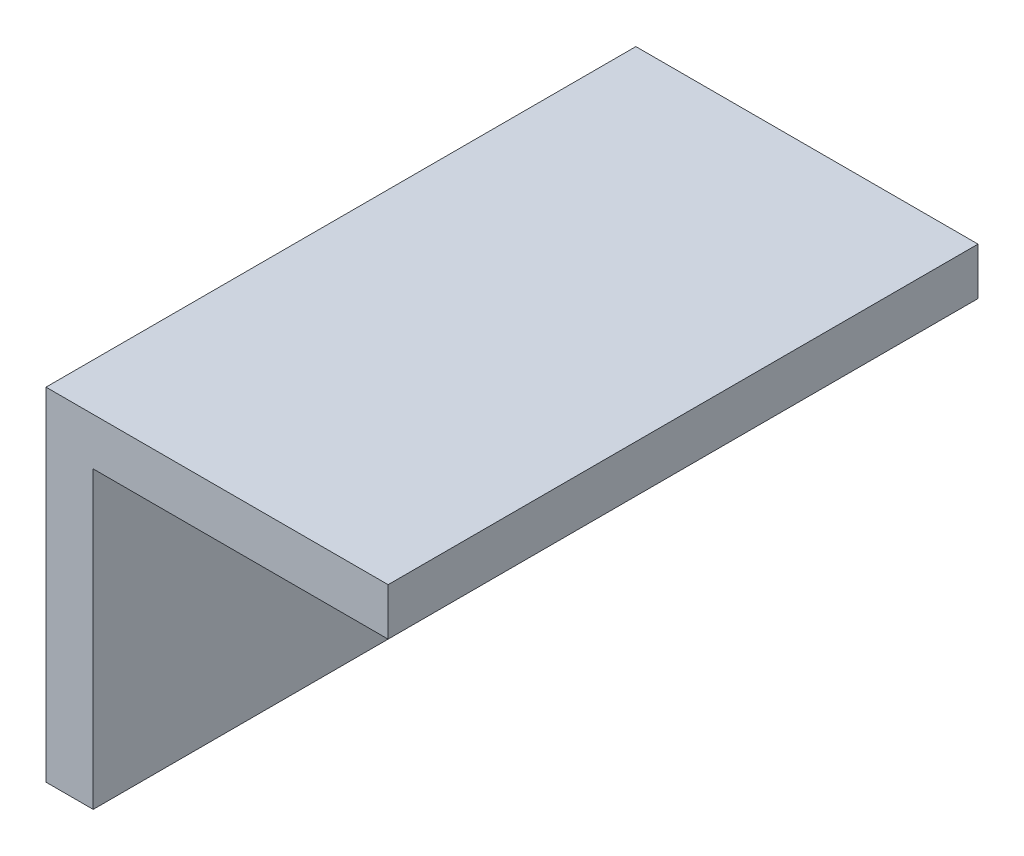
SolidWorks part; units mm, degrees
material "PLA"
ref_plane "Front Plane" through (0, 0, 0) normal (0, 0, 1) x (1, 0, 0)
ref_plane "Top Plane" through (0, 0, 0) normal (0, 1, 0) x (1, 0, 0)
ref_plane "Right Plane" through (0, 0, 0) normal (1, 0, 0) x (0, 0, -1)
sketch "Sketch1" plane through (0, 0, 0) normal (0, 0, 1) x (1, 0, 0)
  line L0 (0, 0) -> (50, 0)
  line L1 (0, 0) -> (0, -50)
  line L2 (-8, 8) -> (-8, -50)
  line L3 (-8, 8) -> (50, 8)
  line L4 (0, -50) -> (-8, -50)
  line L5 (50, 0) -> (50, 8)
  dimension "D1" = 50
  dimension "D2" = 50
  dimension "D3" = 8
extrude "Boss-Extrude1" add sketch "Sketch1" along normal mid plane 100
